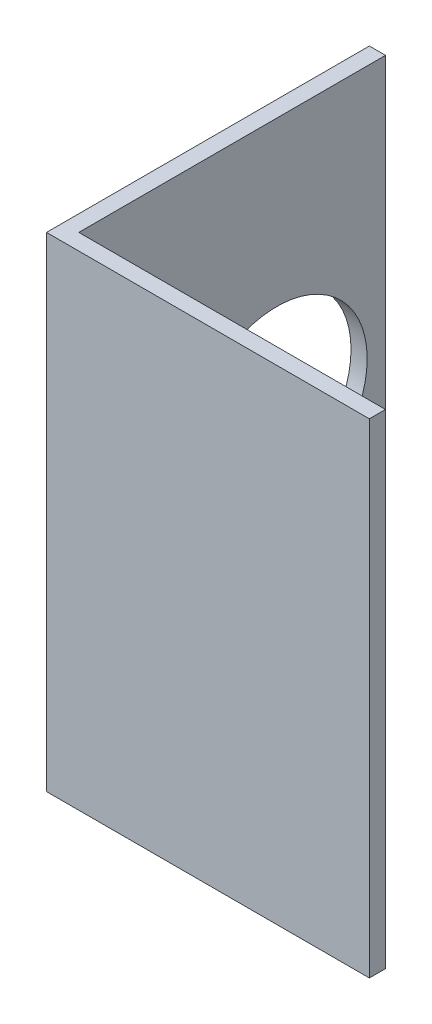
SolidWorks part; units mm, degrees
material "5052-H32"
ref_plane "Front Plane" through (0, 0, 0) normal (0, 0, 1) x (1, 0, 0)
ref_plane "Top Plane" through (0, 0, 0) normal (0, 1, 0) x (1, 0, 0)
ref_plane "Right Plane" through (0, 0, 0) normal (1, 0, 0) x (0, 0, -1)
sketch "Sketch1" plane through (0, 0, 0) normal (0, 1, 0) x (1, 0, 0)
  line L0 (-20.6236, 27.1615) -> (-20.6236, -23.6385)
  line L1 (-20.6236, -23.6385) -> (30.1764, -23.6385)
  line L2 (30.1764, -23.6385) -> (30.1764, -21.0985)
  line L3 (30.1764, -21.0985) -> (-18.0836, -21.0985)
  line L4 (-18.0836, -21.0985) -> (-18.0836, 27.1615)
  line L5 (-18.0836, 27.1615) -> (-20.6236, 27.1615)
  dimension "D1" = 48.26
  dimension "D2" = 50.8
  dimension "D3" = 50.8
  dimension "D4" = 50.8
  dimension "D5" = 48.26
  dimension "D6" = 2.54
extrude "Extrude1" add sketch "Sketch1" along normal blind 76.2
sketch "Sketch3" plane through (-18.0836, 0, 0) normal (1, 0, 0) x (0, 0, -1)
  circle A0 centre (10.0532, 36.2998) radius 14.224
  dimension "D1" = 28.448
extrude "Extrude3" cut sketch "Sketch3" against normal through all
